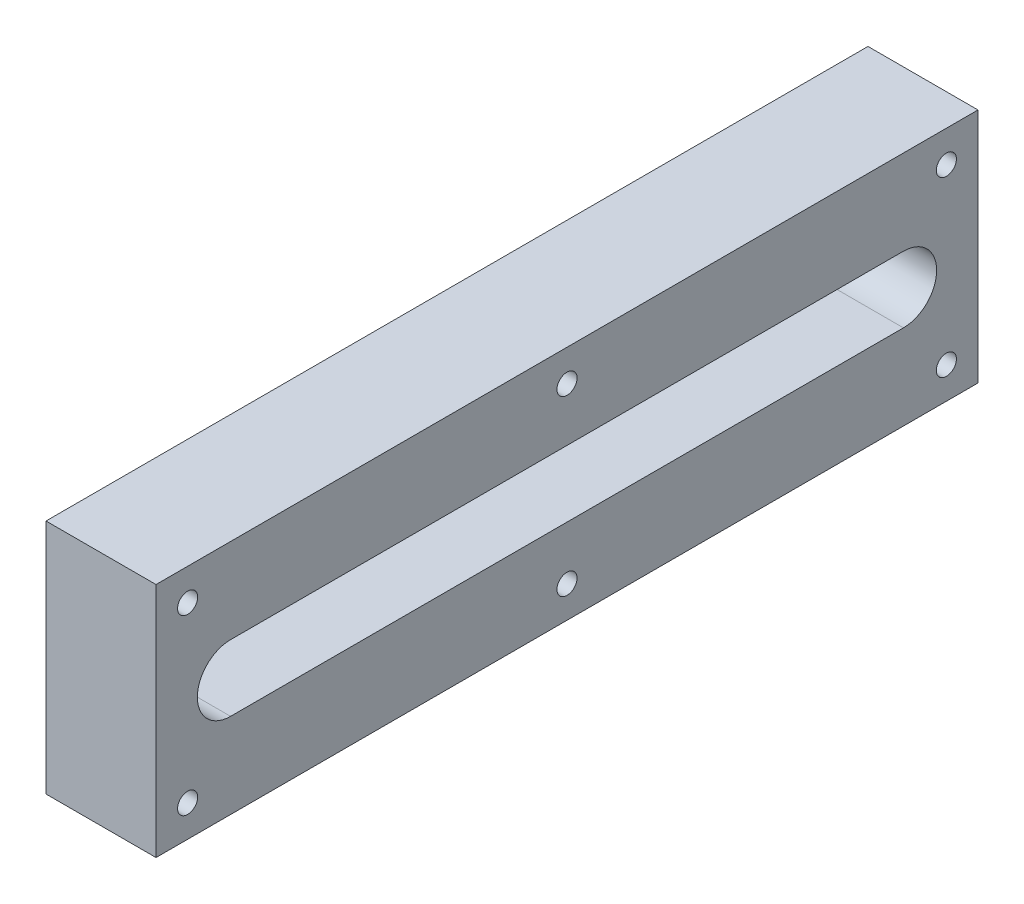
SolidWorks part; units mm, degrees
material "Delrin 2700 NC010, Low Viscosity Acetal Copolymer (SS)"
ref_plane "Front" through (0, 0, 0) normal (0, 0, 1) x (1, 0, 0)
ref_plane "Top" through (0, 0, 0) normal (0, 1, 0) x (1, 0, 0)
ref_plane "Right" through (0, 0, 0) normal (1, 0, 0) x (0, 0, -1)
sketch "Sketch1" plane through (0, 0, 0) normal (1, 0, 0) x (0, 0, -1)
  line L0 (-67.5753, 0) -> (67.5753, 0) construction
  line L1 (82.55, -23.749) -> (-82.55, -23.749)
  line L2 (82.55, -23.749) -> (82.55, 23.749)
  line L3 (82.55, 23.749) -> (-82.55, 23.749)
  line L4 (-82.55, -23.749) -> (-82.55, 23.749)
  line L5 (82.55, -23.749) -> (-82.55, 23.749) construction
  line L6 (82.55, 23.749) -> (-82.55, -23.749) construction
  line L7 (-67.5753, 6.6675) -> (67.5753, 6.6675)
  line L8 (-67.5753, -6.6675) -> (67.5753, -6.6675)
  arc A0 (-67.5753, 6.6675) -> (-67.5753, -6.6675) centre (-67.5753, 0) ccw
  arc A1 (67.5753, -6.6675) -> (67.5753, 6.6675) centre (67.5753, 0) ccw
  point P0 (0, 0)
  point P8 (0, 0)
  dimension "D4" = 13.335
  dimension "D1" = 135.1505
  dimension "D2" = 165.1
  dimension "D3" = 47.498
extrude "Boss-Extrude1" add sketch "Sketch1" along normal blind 22.098
hole_wizard "#10-32 Tapped Hole1" positions "Sketch3" profile "Sketch4" tap size "#10-32" standard "ANSI Inch" end condition through all
sketch "Sketch3" plane through (22.098, 0, 0) normal (1, 0, 0) x (0, 0, -1)
  line L0 (-76.2, 17.399) -> (0, 17.399) construction
  line L1 (0, 17.399) -> (76.2, 17.399) construction
  line L3 (-76.2, 23.749) -> (-76.2, 17.399) construction
  line L4 (82.55, 23.749) -> (-82.55, 23.749) construction
  line L5 (-76.2, 17.399) -> (-76.2, -17.399) construction
  line L6 (-76.2, -17.399) -> (-76.2, -23.749) construction
  line L7 (-82.55, -23.749) -> (82.55, -23.749) construction
  line L8 (-82.55, 23.749) -> (-82.55, -23.749) construction
  point P0 (-76.2, 17.399)
  point P2 (-76.2, -17.399)
  point P4 (0, -17.399)
  point P6 (76.2, -17.399)
  point P8 (76.2, 17.399)
  point P10 (0, 17.399)
  dimension "D1" = 6.35
  dimension "D2" = 6.35
sketch "Sketch4" plane through (22.098, 17.399, 76.2) normal (0, 1, 0) x (0, 0, -1)
  line L0 (0, 0) -> (0, 22.098)
  line L1 (0, 22.098) -> (2.0193, 22.098)
  line L2 (2.0193, 22.098) -> (2.0193, 0)
  line L5 (2.0193, 0) -> (0, 0)
  line L11 (0, -6.35) -> (0, 107.95) construction
  dimension "Thru Tap Drill Dia." = 4.0386
  dimension "Thru Tap Drill Depth" = 22.098
cosmetic thread "Hole Thread1" parameters "D2"=4.826
cosmetic thread "Hole Thread2" parameters "D2"=4.826
cosmetic thread "Hole Thread3" parameters "D2"=4.826
cosmetic thread "Hole Thread4" parameters "D2"=4.826
cosmetic thread "Hole Thread5" parameters "D2"=4.826
cosmetic thread "Hole Thread6" parameters "D2"=4.826
